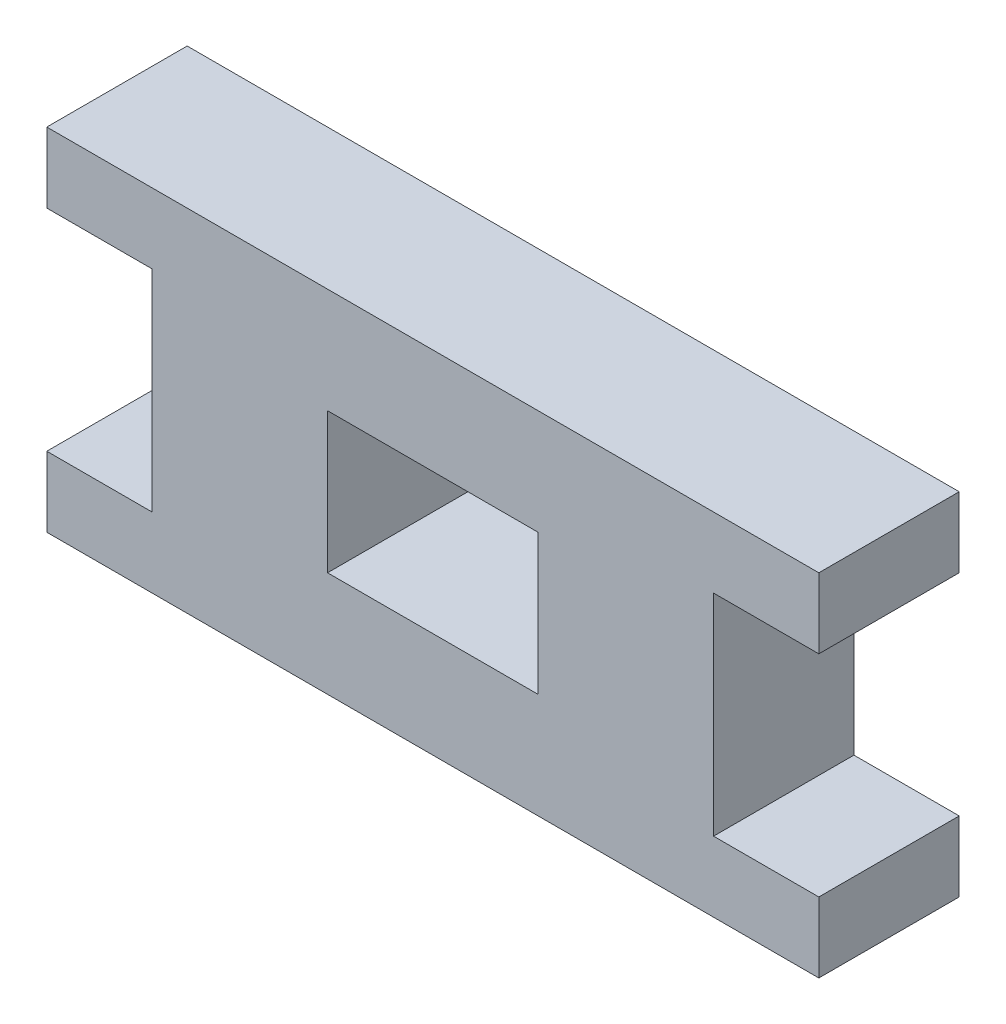
SolidWorks part; units mm, degrees
ref_plane "Front Plane" through (0, 0, 0) normal (0, 0, 1) x (1, 0, 0)
ref_plane "Top Plane" through (0, 0, 0) normal (0, 1, 0) x (1, 0, 0)
ref_plane "Right Plane" through (0, 0, 0) normal (1, 0, 0) x (0, 0, -1)
sketch "Sketch1" plane through (0, 0, 0) normal (0, 0, 1) x (1, 0, 0)
  line L1 (-15, 10) -> (15, 10)
  line L2 (-15, 10) -> (-15, -10)
  line L3 (-15, -10) -> (15, -10)
  line L4 (15, 10) -> (15, -10)
  line L7 (-40, -25) -> (40, -25)
  line L8 (-40, -15) -> (-40, 15)
  line L9 (-40, 25) -> (40, 25)
  line L10 (40, -15) -> (40, 15)
  line L13 (40, 25) -> (55, 25)
  line L15 (40, 15) -> (55, 15)
  line L16 (55, 25) -> (55, 15)
  line L18 (-55, 25) -> (-55, 15)
  line L19 (-40, 15) -> (-55, 15)
  line L21 (-40, 25) -> (-55, 25)
  line L22 (-40, -25) -> (-55, -25)
  line L24 (-40, -15) -> (-55, -15)
  line L25 (-55, -25) -> (-55, -15)
  line L26 (55, -25) -> (55, -15)
  line L27 (40, -15) -> (55, -15)
  line L29 (40, -25) -> (55, -25)
  point P0 (0, 0)
  point P6 (0, 0)
  dimension "D1" = 30
  dimension "D2" = 20
  dimension "D3" = 50
  dimension "D4" = 80
  dimension "D5" = 15
  dimension "D6" = 10
extrude "Boss-Extrude1" add sketch "Sketch1" along normal blind 20
